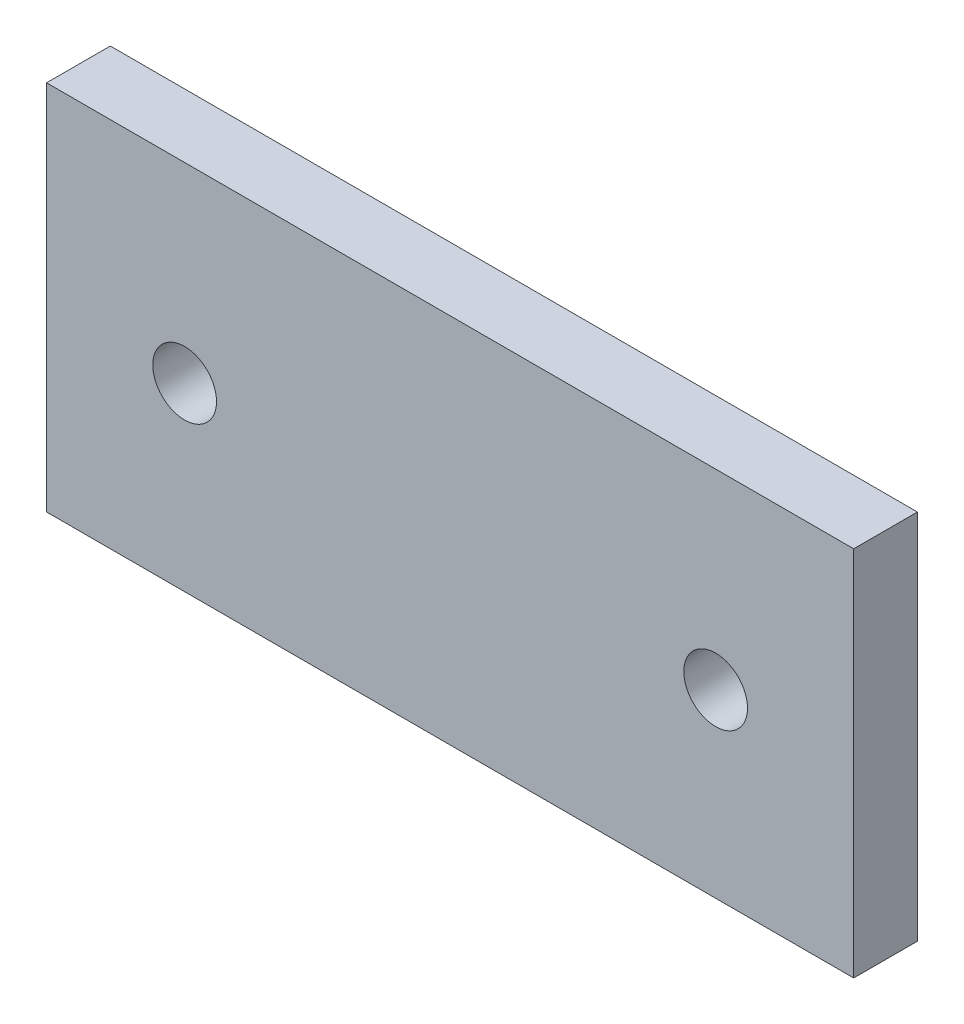
SolidWorks part; units mm, degrees
ref_plane "Front Plane" through (0, 0, 0) normal (0, 0, 1) x (1, 0, 0)
ref_plane "Top Plane" through (0, 0, 0) normal (0, 1, 0) x (1, 0, 0)
ref_plane "Right Plane" through (0, 0, 0) normal (1, 0, 0) x (0, 0, -1)
sketch "Sketch1" plane through (0, 0, 0) normal (0, 0, 1) x (1, 0, 0)
  line L1 (0, 0) -> (-76, 0)
  line L2 (0, 0) -> (0, 35)
  line L3 (0, 35) -> (-76, 35)
  line L4 (-76, 0) -> (-76, 35)
  line L5 (0, 0) -> (-76, 35) construction
  line L6 (0, 35) -> (-76, 0) construction
  point P4 (-38, 17.5)
  dimension "D1" = 76
  dimension "D2" = 35
extrude "Boss-Extrude1" add sketch "Sketch1" along normal blind 6
sketch "Sketch2" plane through (0, 0, 6) normal (0, 0, 1) x (1, 0, 0)
  line L0 (0, 0) -> (0, 35) construction
  line L1 (0, 35) -> (-76, 35) construction
  line L2 (-76, 35) -> (-76, 0) construction
  circle A0 centre (-13, 17) radius 3
  circle A1 centre (-63, 17) radius 3
  dimension "D3" = 6
  dimension "D6" = 6
  dimension "D1" = 13
  dimension "D2" = 18
  dimension "D4" = 18
  dimension "D5" = 13
extrude "Cut-Extrude1" cut sketch "Sketch2" against normal blind 6
